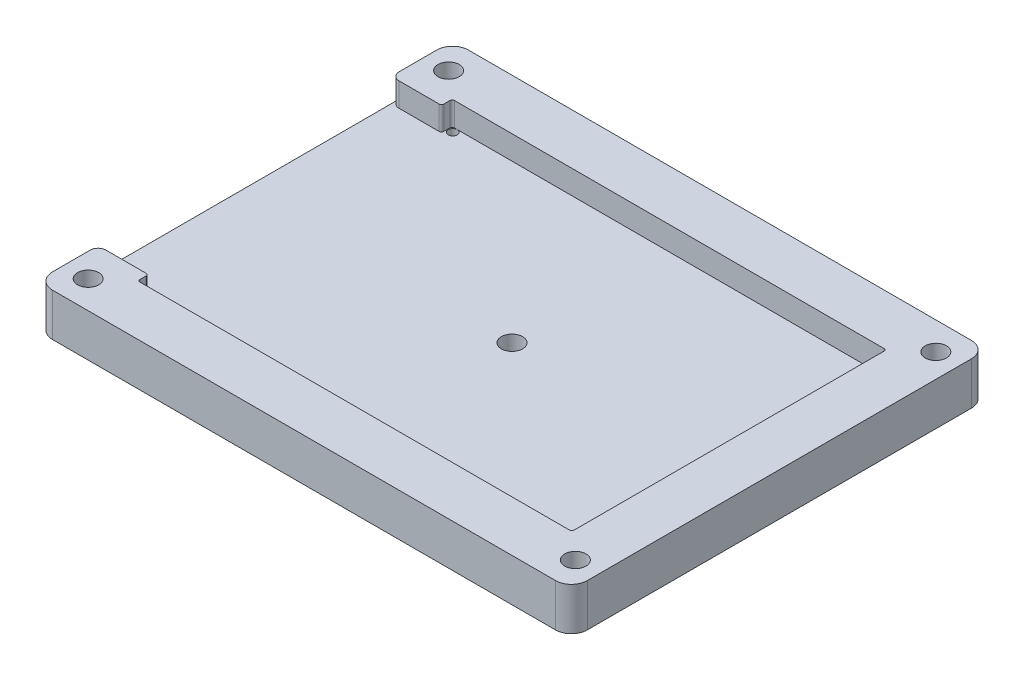
SolidWorks part; units mm, degrees
ref_plane "Front Plane" through (0, 0, 0) normal (0, 0, 1) x (1, 0, 0)
ref_plane "Top Plane" through (0, 0, 0) normal (0, 1, 0) x (1, 0, 0)
ref_plane "Right Plane" through (0, 0, 0) normal (1, 0, 0) x (0, 0, -1)
sketch "Sketch1" plane through (0, 0, 0) normal (0, 1, 0) x (1, 0, 0)
  line L1 (-42.8625, -33.3375) -> (42.8625, -33.3375)
  line L2 (-42.8625, -33.3375) -> (-42.8625, 33.3375)
  line L3 (-42.8625, 33.3375) -> (42.8625, 33.3375)
  line L4 (42.8625, -33.3375) -> (42.8625, 33.3375)
  line L5 (-42.8625, -33.3375) -> (42.8625, 33.3375) construction
  line L6 (-42.8625, 33.3375) -> (42.8625, -33.3375) construction
  point P0 (0, 0)
  dimension "D1" = 85.725
  dimension "D2" = 66.675
extrude "Boss-Extrude1" add sketch "Sketch1" along normal blind 6.858
fillet "Fillet1" radius 2.54 4 edges at (42.8625, 3.429, 33.3375) (-42.8625, 3.429, -33.3375) (42.8625, 3.429, -33.3375) (-42.8625, 3.429, 33.3375)
sketch "Sketch2" plane through (0, 6.858, 0) normal (0, 1, 0) x (1, 0, 0)
  line L1 (34.798, -25.2095) -> (-34.798, -25.2095)
  line L2 (34.798, -25.2095) -> (34.798, 25.2095)
  line L3 (34.798, 25.2095) -> (-34.798, 25.2095)
  line L4 (-34.798, -25.2095) -> (-34.798, 25.2095)
  line L5 (34.798, -25.2095) -> (-34.798, 25.2095) construction
  line L6 (34.798, 25.2095) -> (-34.798, -25.2095) construction
  point P0 (0, 0)
  dimension "D1" = 69.596
  dimension "D2" = 50.419
extrude "Cut-Extrude1" cut sketch "Sketch2" against normal blind 3.81
fillet "Fillet2" radius 0.381 4 edges at (34.798, 4.953, 25.2095) (34.798, 4.953, -25.2095) (-34.798, 4.953, 25.2095) (-34.798, 4.953, -25.2095)
sketch "Sketch3" plane through (0, 3.048, 0) normal (0, 1, 0) x (1, 0, 0)
  line L0 (-33.9725, 24.4729) -> (-33.9725, -24.4729) construction
  line L1 (-33.9725, -24.4729) -> (33.9725, -24.4729) construction
  line L2 (33.9725, -24.4729) -> (33.9725, 24.4729) construction
  line L3 (33.9725, 24.4729) -> (-33.9725, 24.4729) construction
  line L4 (0, -3.7719) -> (0, 3.7719) construction
  line L5 (-3.7719, 0) -> (3.7719, 0) construction
  circle A0 centre (-33.9725, 24.4729) radius 0.7239
  circle A1 centre (33.9725, 24.4729) radius 0.7239
  circle A2 centre (33.9725, -24.4729) radius 0.7239
  circle A3 centre (-33.9725, -24.4729) radius 0.7239
  point P8 (0, 24.4729)
  point P11 (-33.9725, 0)
  dimension "D3" = 1.4478
  dimension "D1" = 67.945
  dimension "D2" = 48.9458
extrude "Cut-Extrude2" cut sketch "Sketch3" against normal blind 3.556
hole_wizard "M3 Clearance Hole1" positions "Sketch4" profile "Sketch5" hole size "M3" standard "ANSI Metric" end condition up to next
sketch "Sketch4" plane through (0, 0, 0) normal (0, -1, 0) x (-1, 0, 0)
  line L1 (-39.0525, -28.8925) -> (39.0525, -28.8925) construction
  line L2 (-39.0525, -28.8925) -> (-39.0525, 28.8925) construction
  line L3 (-39.0525, 28.8925) -> (39.0525, 28.8925) construction
  line L4 (39.0525, -28.8925) -> (39.0525, 28.8925) construction
  line L5 (-39.0525, -28.8925) -> (39.0525, 28.8925) construction
  line L6 (-39.0525, 28.8925) -> (39.0525, -28.8925) construction
  point P0 (-39.0525, 28.8925)
  point P3 (0, 0)
  point P4 (39.0525, 28.8925)
  point P275 (-39.0525, -28.8925)
  point P277 (39.0525, -28.8925)
  dimension "D1" = 78.105
  dimension "D2" = 57.785
sketch "Sketch5" plane through (39.0525, 0, -28.8925) normal (1, 0, 0) x (0, 0, -1)
  line L0 (0, 0) -> (0, 6.858)
  line L1 (0, 6.858) -> (1.7, 6.858)
  line L2 (1.7, 6.858) -> (1.7, 0)
  line L5 (1.7, 0) -> (0, 0)
  line L11 (0, -6.35) -> (0, 107.95) construction
  dimension "Thru Hole Dia." = 3.4
  dimension "Thru Hole Depth" = 6.858
sketch "Sketch6" plane through (0, 6.858, 0) normal (0, 1, 0) x (1, 0, 0)
  line L0 (-3.7719, 0) -> (3.7719, 0) construction
  line L9 (-66.0616, 23.495) -> (-19.6685, 23.495)
  line L10 (-66.0616, 23.495) -> (-66.0616, -23.495)
  line L11 (-66.0616, -23.495) -> (-19.6685, -23.495)
  line L12 (-19.6685, 23.495) -> (-19.6685, -23.495)
  point P4 (-19.6685, 0)
  dimension "D1" = 46.99
extrude "Cut-Extrude3" cut sketch "Sketch6" against normal up to surface (3.81 mm away) up to face at (0, 3.048, 1.7)
fillet "Fillet3" radius 0.381 2 edges at (-34.798, 4.953, 23.495) (-34.798, 4.953, -23.495)
fillet "Fillet4" radius 1.27 2 edges at (-42.8625, 4.953, -23.495) (-42.8625, 4.953, 23.495)
